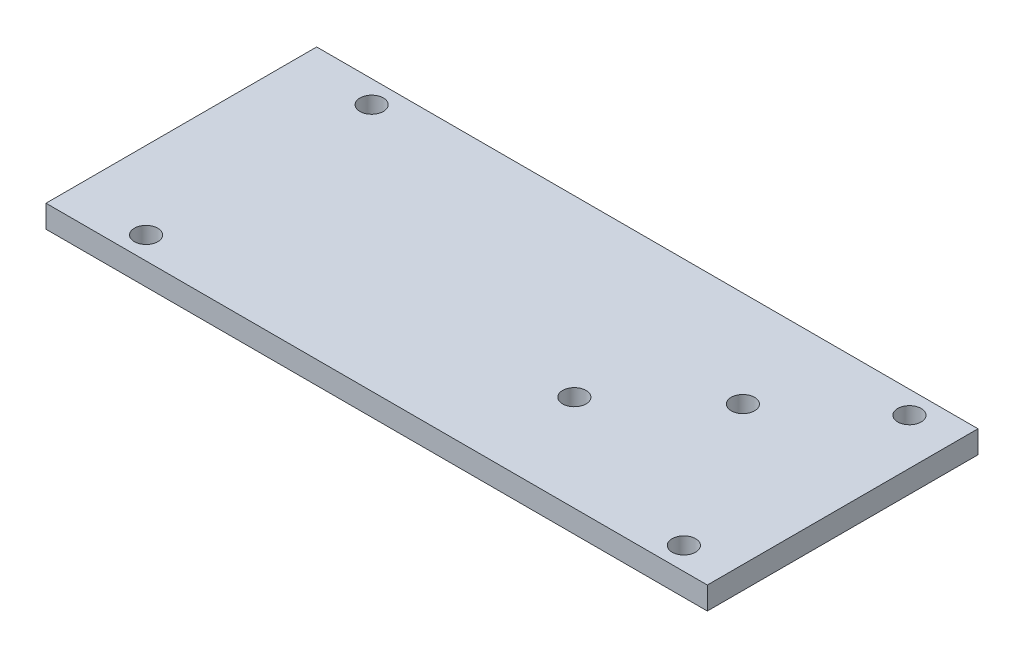
SolidWorks part; units mm, degrees
ref_plane "Front Plane" through (0, 0, 0) normal (0, 0, 1) x (1, 0, 0)
ref_plane "Top Plane" through (0, 0, 0) normal (0, 1, 0) x (1, 0, 0)
ref_plane "Right Plane" through (0, 0, 0) normal (1, 0, 0) x (0, 0, -1)
sketch "Sketch1" plane through (0, 0, 0) normal (0, 1, 0) x (1, 0, 0)
  line L1 (-46.5455, -19.05) -> (46.5455, -19.05)
  line L2 (-46.5455, -19.05) -> (-46.5455, 19.05)
  line L3 (-46.5455, 19.05) -> (46.5455, 19.05)
  line L4 (46.5455, -19.05) -> (46.5455, 19.05)
  line L5 (-46.5455, -19.05) -> (46.5455, 19.05) construction
  line L6 (-46.5455, 19.05) -> (46.5455, -19.05) construction
  circle A0 centre (40.0685, 15.875) radius 1.651
  circle A1 centre (40.0685, -15.875) radius 1.651
  circle A2 centre (-35.6312, -15.875) radius 1.651
  circle A3 centre (-35.6312, 15.875) radius 1.651
  circle A4 centre (-35.6312, 15.875) radius 1.651 construction
  circle A5 centre (26.9875, 5.5118) radius 1.651
  circle A6 centre (14.2875, -5.5118) radius 1.651
  point P0 (0, 0)
  dimension "D1" = 93.091
  dimension "D2" = 38.1
extrude "Boss-Extrude1" add sketch "Sketch1" along normal blind 3.175
